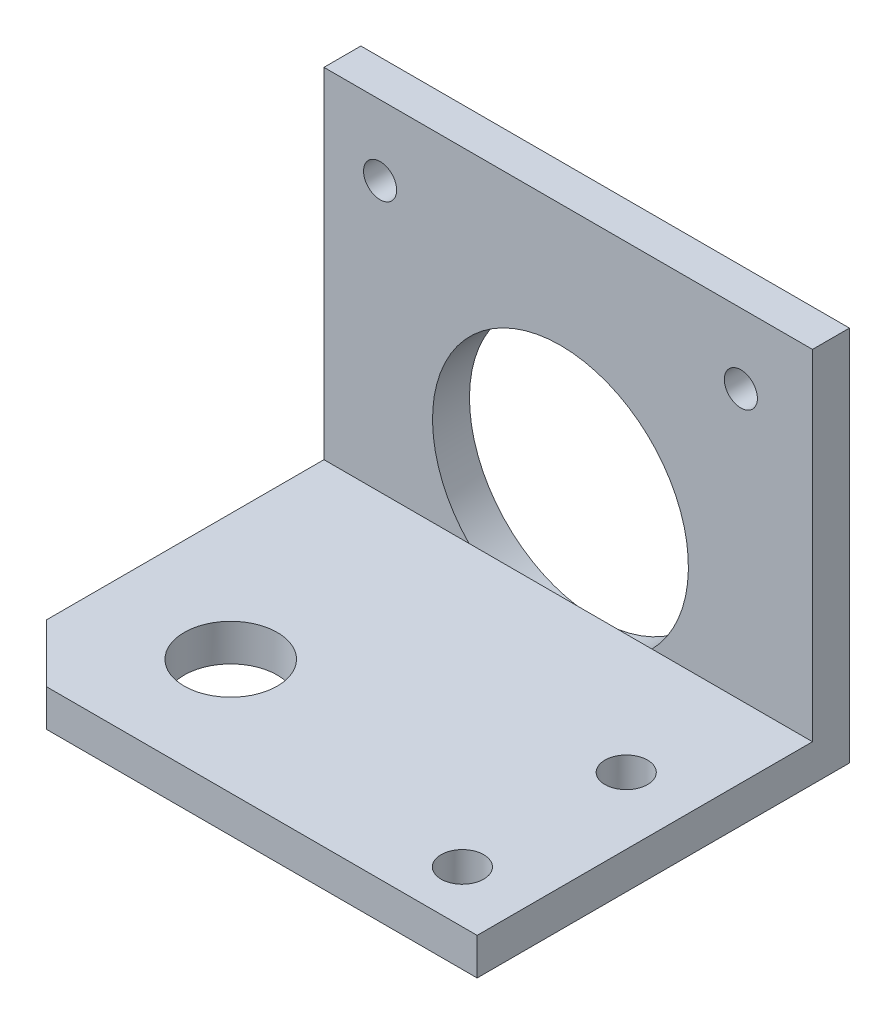
SolidWorks part; units mm, degrees
ref_plane "Front Plane" through (0, 0, 0) normal (0, 0, 1) x (1, 0, 0)
ref_plane "Top Plane" through (0, 0, 0) normal (0, 1, 0) x (1, 0, 0)
ref_plane "Right Plane" through (0, 0, 0) normal (1, 0, 0) x (0, 0, -1)
sketch "Sketch1" plane through (0, 0, 0) normal (0, 1, 0) x (1, 0, 0)
  line L1 (-21, -16.002) -> (21, -16.002)
  line L2 (-21, -16.002) -> (-21, 16.002)
  line L3 (-21, 16.002) -> (21, 16.002)
  line L4 (21, -16.002) -> (21, 16.002)
  line L5 (-21, -16.002) -> (21, 16.002) construction
  line L6 (-21, 16.002) -> (21, -16.002) construction
  point P0 (0, 0)
extrude "Boss-Extrude1" add sketch "Sketch1" along normal blind 3.175
sketch "Sketch2" plane through (0, 0, -16.002) normal (0, 0, -1) x (-1, 0, 0)
  line L0 (21, 3.175) -> (21, 0) construction
  line L1 (-21, 0) -> (21, 0)
  line L2 (-21, 0) -> (-21, 32.385)
  line L3 (-21, 32.385) -> (21, 32.385)
  line L4 (21, 0) -> (21, 32.385)
extrude "Boss-Extrude2" add sketch "Sketch2" against normal blind 3.175
sketch "Sketch3" plane through (0, 0, -12.827) normal (0, 0, 1) x (1, 0, 0)
  circle A1 centre (-0.666, 10.8585) radius 10.9982
  circle A2 centre (-16.1727, 26.3652) radius 1.4224
  circle A3 centre (14.8407, 26.3652) radius 1.4224
extrude "Cut-Extrude1" cut sketch "Sketch3" against normal blind 5.08
sketch "Sketch4" plane through (0, 3.175, 0) normal (0, 1, 0) x (1, 0, 0)
  circle A0 centre (-10.1465, -6.0381) radius 4.0005
  circle A3 centre (15.2705, -11.541) radius 1.8288
  circle A5 centre (15.2705, 2.5456) radius 1.8288
  dimension "D3" = 25.417
extrude "Cut-Extrude2" cut sketch "Sketch4" against normal blind 5.1054
sketch "Sketch5" plane through (0, 3.175, 0) normal (0, 1, 0) x (1, 0, 0)
  line L0 (-16.0153, -16.002) -> (-21, -11.0173)
  line L1 (-21, -16.002) -> (21, -16.002) construction
  line L2 (-21, 12.827) -> (-21, -16.002) construction
  line L3 (-21, -11.0173) -> (-21, -16.002)
  line L4 (-21, -16.002) -> (-16.0153, -16.002)
extrude "Cut-Extrude3" cut sketch "Sketch5" against normal through all
